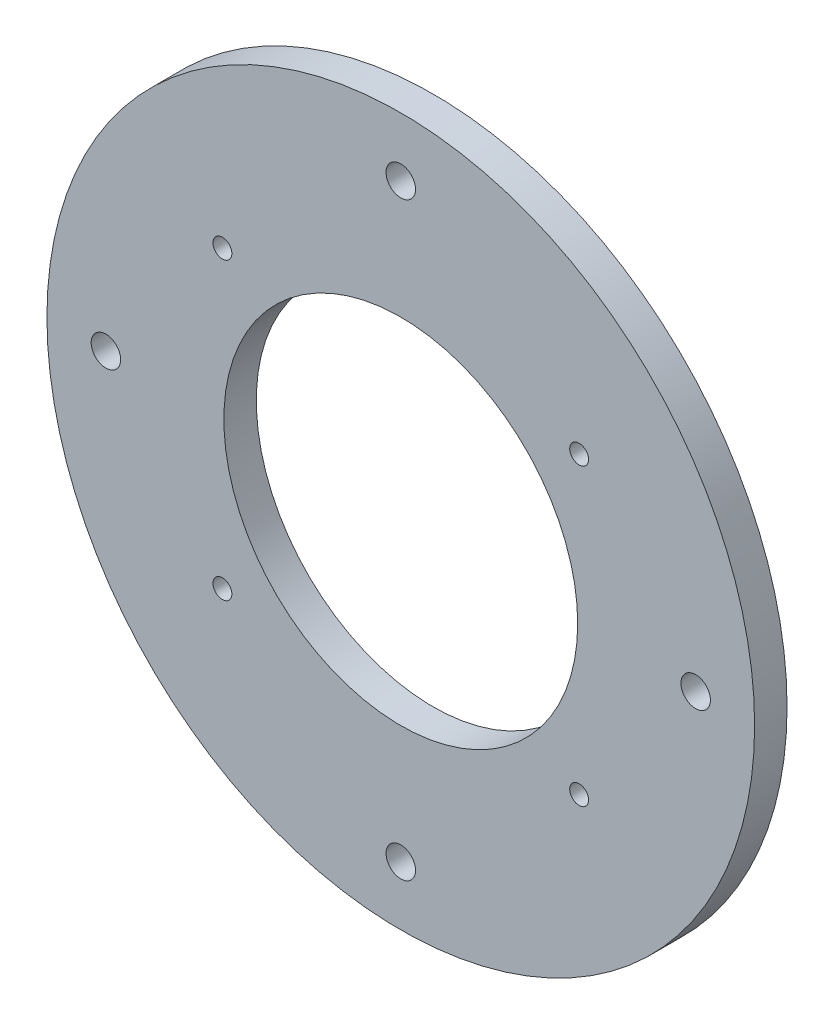
SolidWorks part; units mm, degrees
ref_plane "正面" through (0, 0, 0) normal (0, 0, 1) x (1, 0, 0)
ref_plane "平面" through (0, 0, 0) normal (0, 1, 0) x (1, 0, 0)
ref_plane "右側面" through (0, 0, 0) normal (1, 0, 0) x (0, 0, -1)
sketch "ｽｹｯﾁ1" plane through (0, 0, 0) normal (0, 0, 1) x (1, 0, 0)
  circle A0 centre (0, 0) radius 60
  circle A1 centre (0, 0) radius 30
  dimension "D1" = 120
  dimension "D2" = 60
extrude "ﾎﾞｽ - 押し出し1" add sketch "ｽｹｯﾁ1" along normal blind 5.5
sketch "ｽｹｯﾁ2" plane through (0, 0, 5.5) normal (0, 0, 1) x (1, 0, 0)
  circle A0 centre (0, -50) radius 2.5 construction
  circle A1 centre (-50, 0) radius 2.5 construction
  circle A2 centre (50, 0) radius 2.5 construction
  circle A3 centre (0, 50) radius 2.5 construction
  circle A4 centre (0, -50) radius 2.5
  circle A5 centre (-50, 0) radius 2.5
  circle A6 centre (50, 0) radius 2.5
  circle A7 centre (0, 50) radius 2.5
extrude "ｶｯﾄ - 押し出し1" cut sketch "ｽｹｯﾁ2" against normal through all both and the other way through all
sketch "ｽｹｯﾁ3" plane through (0, 0, 5.5) normal (0, 0, 1) x (1, 0, 0)
  circle A0 centre (30.2458, 25) radius 1.6 construction
  circle A3 centre (30.2458, 25) radius 1.6
  circle A4 centre (-30.2458, 25) radius 1.6 construction
  circle A5 centre (-30.2458, -25) radius 1.6 construction
  circle A6 centre (30.2458, -25) radius 1.6 construction
  circle A7 centre (-30.2458, 25) radius 1.6
  circle A8 centre (-30.2458, -25) radius 1.6
  circle A9 centre (30.2458, -25) radius 1.6
extrude "ｶｯﾄ - 押し出し3" cut sketch "ｽｹｯﾁ3" against normal through all both
